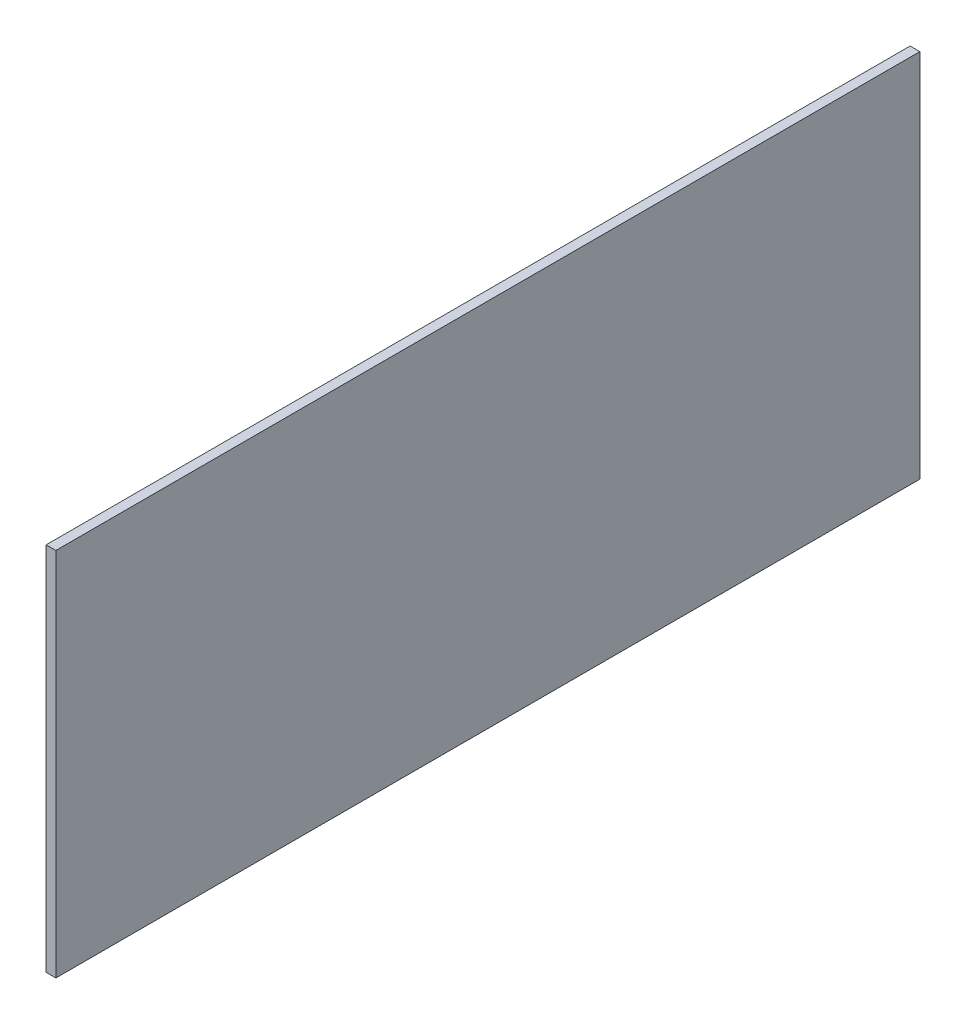
SolidWorks part; units mm, degrees
ref_plane "Front Plane" through (0, 0, 0) normal (0, 0, 1) x (1, 0, 0)
ref_plane "Top Plane" through (0, 0, 0) normal (0, 1, 0) x (1, 0, 0)
ref_plane "Right Plane" through (0, 0, 0) normal (1, 0, 0) x (0, 0, -1)
sketch "Sketch1" plane through (0, 0, 0) normal (1, 0, 0) x (0, 0, -1)
  line L1 (-88.9, 38.1) -> (88.9, 38.1)
  line L2 (-88.9, 38.1) -> (-88.9, -38.1)
  line L3 (-88.9, -38.1) -> (88.9, -38.1)
  line L4 (88.9, 38.1) -> (88.9, -38.1)
  line L5 (-88.9, 38.1) -> (88.9, -38.1) construction
  line L6 (-88.9, -38.1) -> (88.9, 38.1) construction
  point P0 (0, 0)
extrude "Boss-Extrude1" add sketch "Sketch1" along normal blind 2
